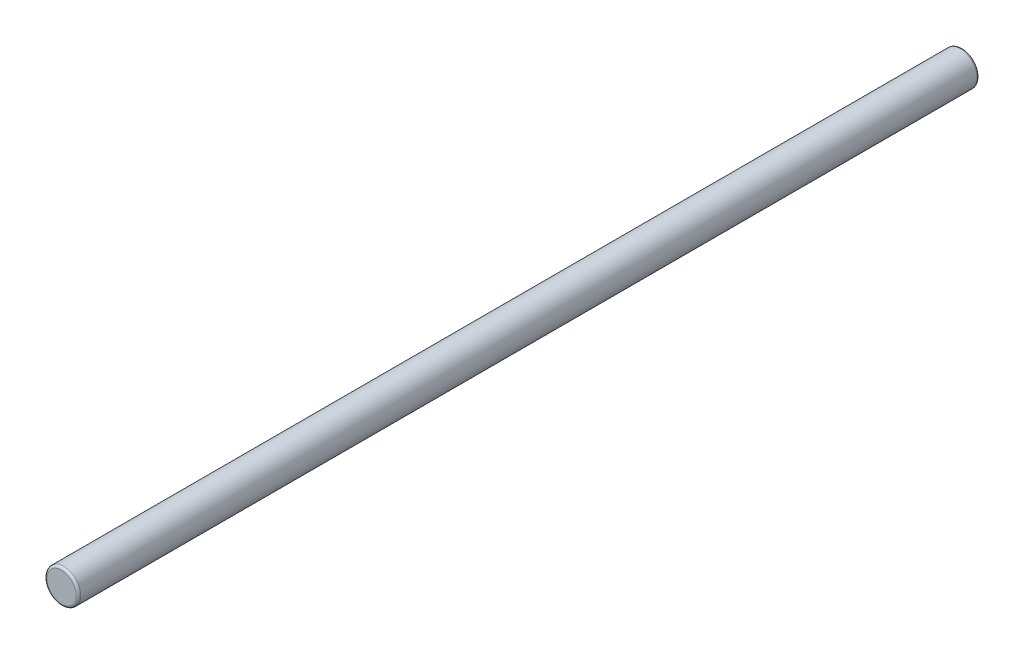
SolidWorks part; units mm, degrees
ref_plane "Front Plane" through (0, 0, 0) normal (0, 0, 1) x (1, 0, 0)
ref_plane "Top Plane" through (0, 0, 0) normal (0, 1, 0) x (1, 0, 0)
ref_plane "Right Plane" through (0, 0, 0) normal (1, 0, 0) x (0, 0, -1)
sketch "Sketch1" plane through (0, 0, 0) normal (0, 0, 1) x (1, 0, 0)
  circle A0 centre (0, 0) radius 0.75
  dimension "D1" = 1.5
extrude "Boss-Extrude1" add sketch "Sketch1" along normal blind 40
fillet "Fillet1" radius 0.1 1 edges at (0.75, 0, 40)
fillet "Fillet2" radius 0.1 1 edges at (0.75, 0, 0)
